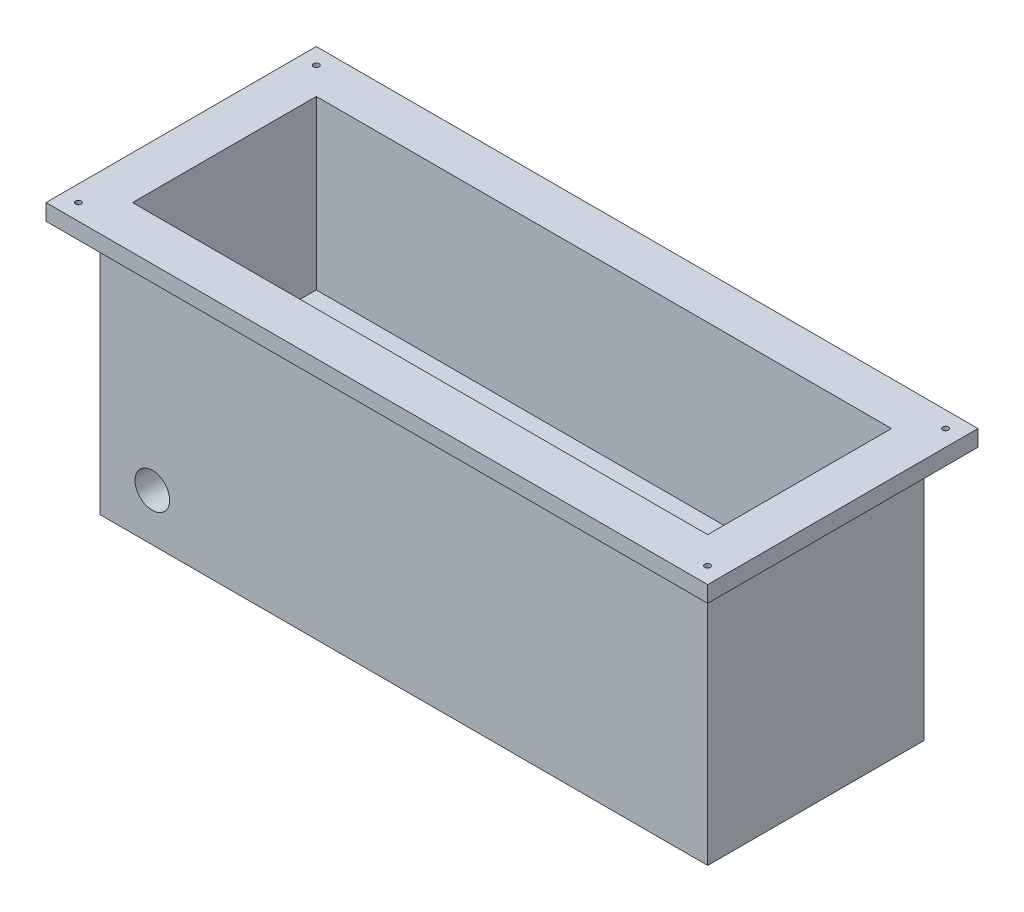
SolidWorks part; units mm, degrees
ref_plane "Front Plane" through (0, 0, 0) normal (0, 0, 1) x (1, 0, 0)
ref_plane "Top Plane" through (0, 0, 0) normal (0, 1, 0) x (1, 0, 0)
ref_plane "Right Plane" through (0, 0, 0) normal (1, 0, 0) x (0, 0, -1)
sketch "Sketch1" plane through (0, 0, 0) normal (0, 1, 0) x (1, 0, 0)
  line L1 (0, 0) -> (142.748, 0)
  line L2 (0, 0) -> (0, 50.8)
  line L3 (0, 50.8) -> (142.748, 50.8)
  line L4 (142.748, 0) -> (142.748, 50.8)
  dimension "D1" = 142.748
  dimension "D2" = 50.8
extrude "Boss-Extrude1" add sketch "Sketch1" along normal blind 63.5 contours L2 L3 L4 L1
shell "Shell1" thickness 3.81
sketch "Sketch2" plane through (0, 0, 0) normal (0, 0, 1) x (1, 0, 0)
  line L0 (0, 63.5) -> (0, 0) construction
  line L1 (-6.35, 63.5) -> (149.098, 63.5)
  line L2 (-6.35, 63.5) -> (-6.35, 59.69)
  line L3 (-6.35, 59.69) -> (149.098, 59.69)
  line L4 (149.098, 63.5) -> (149.098, 59.69)
  line L5 (142.748, 63.5) -> (142.748, 0) construction
  line L6 (0, 63.5) -> (142.748, 63.5) construction
  dimension "D1" = 6.35
  dimension "D2" = 6.35
  dimension "D3" = 3.81
extrude "Boss-Extrude2" add sketch "Sketch2" along normal blind 6.35 contours L1 L4 L3 L2
sketch "Sketch3" plane through (0, 0, -50.8) normal (0, 0, -1) x (-1, 0, 0)
  line L1 (-149.098, 63.5) -> (6.35, 63.5)
  line L2 (-149.098, 63.5) -> (-149.098, 59.69)
  line L3 (-149.098, 59.69) -> (6.35, 59.69)
  line L4 (6.35, 63.5) -> (6.35, 59.69)
extrude "Boss-Extrude3" add sketch "Sketch3" along normal blind 6.35
sketch "Sketch4" plane through (0, 0, 0) normal (-1, 0, 0) x (0, 0, 1)
  line L1 (-50.8, 63.5) -> (0, 63.5)
  line L2 (-50.8, 63.5) -> (-50.8, 59.69)
  line L3 (-50.8, 59.69) -> (0, 59.69)
  line L4 (0, 63.5) -> (0, 59.69)
extrude "Boss-Extrude4" add sketch "Sketch4" along normal blind 6.35
sketch "Sketch5" plane through (142.748, 0, 0) normal (1, 0, 0) x (0, 0, -1)
  line L1 (0, 63.5) -> (50.8, 63.5)
  line L2 (0, 63.5) -> (0, 59.69)
  line L3 (0, 59.69) -> (50.8, 59.69)
  line L4 (50.8, 63.5) -> (50.8, 59.69)
extrude "Boss-Extrude5" add sketch "Sketch5" along normal blind 6.35
hole_wizard "CBORE for #00 Binding Head Machine Screw3" positions "3DSketch3" profile "Sketch11" counterbore size "#00" standard "ANSI Inch" end condition through all
sketch3d "3DSketch3"
  line L0 (-6.35, 59.69, 6.35) -> (149.098, 59.69, 6.35) construction
  line L1 (-6.35, 59.69, 6.35) -> (-6.35, 59.69, -57.15) construction
  line L2 (149.098, 59.69, -57.15) -> (-6.35, 59.69, -57.15) construction
  line L3 (149.098, 59.69, 6.35) -> (149.098, 59.69, -57.15) construction
  point P0 (-2.54, 59.69, 2.54)
  point P2 (145.26, 59.69, 2.54)
  point P4 (145.288, 59.69, -53.34)
  point P6 (-2.54, 59.69, -53.34)
  dimension "D1" = 3.81
  dimension "D2" = 3.81
  dimension "D3" = 3.81
  dimension "D4" = 3.81
  dimension "D5" = 3.81
  dimension "D6" = 3.81
  dimension "D7" = 3.81
  dimension "D8" = 3.838
sketch "Sketch11" plane through (-2.54, 59.69, 2.54) normal (1, 0, 0) x (0, 0, -1)
  line L0 (0, 0) -> (0, 3.81)
  line L1 (0, 3.81) -> (0.6604, 3.81)
  line L3 (0.6604, 3.81) -> (0.6604, 0.7112)
  line L4 (1.5875, 0.7112) -> (0.6604, 0.7112)
  line L5 (1.5875, 0.7112) -> (1.5875, 0.5328)
  line L6 (1.5875, 0.5328) -> (2.2225, 0)
  line L7 (2.2225, 0) -> (0, 0)
  line L8 (-1.5875, 0.5328) -> (-2.2225, 0) construction
  line L11 (0, -6.35) -> (0, 107.95) construction
  dimension "Thru Hole Dia." = 1.3208
  dimension "Thru Hole Depth" = 3.81
  dimension "C'Bore Dia." = 3.175
  dimension "C'Bore Depth" = 0.7112
  dimension "Near C'Sink Dia." = 4.445
  dimension "Near C'Sink Angle" = 100
ref_plane "Plane1" through (-6.35, 63.5, -57.15) normal (0, 1, 0) x (1, 0, 0)
sketch "Sketch13" plane through (0, 3.81, 0) normal (0, 1, 0) x (1, 0, 0)
  line L0 (138.938, 3.81) -> (138.938, 46.99) construction
  line L1 (3.81, 46.99) -> (138.938, 46.99)
  line L2 (3.81, 46.99) -> (3.81, 40.386)
  line L3 (3.81, 40.386) -> (138.938, 40.386)
  line L4 (138.938, 46.99) -> (138.938, 40.386)
  line L6 (3.81, 3.81) -> (138.938, 3.81)
  line L7 (3.81, 3.81) -> (3.81, 10.414)
  line L8 (3.81, 10.414) -> (138.938, 10.414)
  line L9 (138.938, 3.81) -> (138.938, 10.414)
  dimension "D1" = 6.604
  dimension "D2" = 6.604
extrude "Boss-Extrude6" add sketch "Sketch13" along normal blind 20.32
sketch "Sketch14" plane through (0, 0, 0) normal (0, 0, 1) x (1, 0, 0)
  circle A0 centre (12.2805, 11.1077) radius 4.0728
extrude "Cut-Extrude1" cut sketch "Sketch14" against normal blind 13.97
